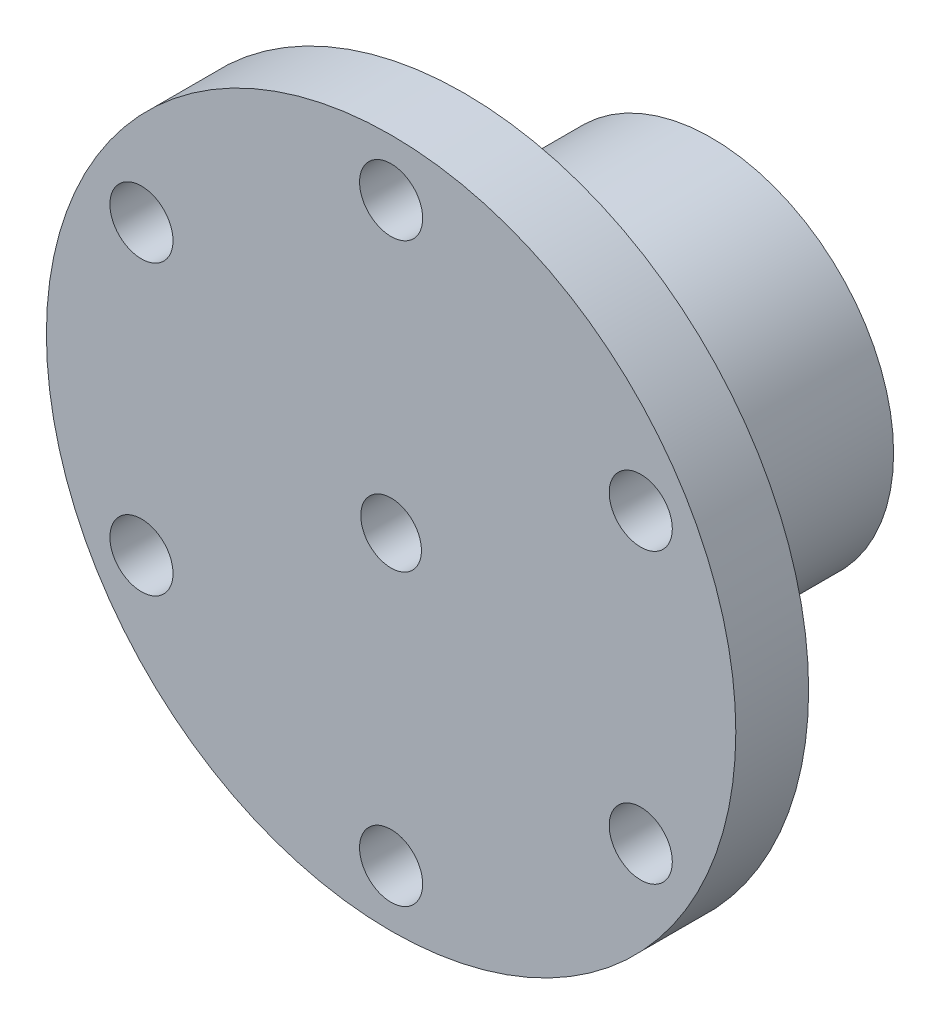
SolidWorks part; units mm, degrees
ref_plane "前视基准面" through (0, 0, 0) normal (0, 0, 1) x (1, 0, 0)
ref_plane "上视基准面" through (0, 0, 0) normal (0, 1, 0) x (1, 0, 0)
ref_plane "右视基准面" through (0, 0, 0) normal (1, 0, 0) x (0, 0, -1)
other "Configuration Table"
sketch "草图1" plane through (0, 0, 0) normal (0, 1, 0) x (1, 0, 0)
  line L0 (0, 0) -> (0, 26.4)
  line L1 (0, 26.4) -> (15, 26.4)
  line L2 (15, 26.4) -> (15, 6)
  line L3 (15, 6) -> (28.4, 6)
  line L4 (28.4, 6) -> (28.4, 0)
  line L5 (28.4, 0) -> (0, 0)
  dimension "D1" = 28.4
  dimension "D2" = 6
  dimension "D3" = 15
  dimension "D4" = 20.4
revolve "旋转1" add sketch "草图1" angle 360 about L0
sketch "草图2" plane through (0, 0, -26.4) normal (0, 0, -1) x (-1, 0, 0)
  circle A0 centre (0, 0) radius 2.5
  dimension "D1" = 5
extrude "切除-拉伸1" cut sketch "草图2" against normal through all
sketch "草图3" plane through (0, 0, 0) normal (0, 1, 0) x (1, 0, 0)
  circle A0 centre (0, 14.3702) radius 3
  dimension "D1" = 6
extrude "切除-拉伸2" cut sketch "草图3" against normal through all
sketch "草图4" plane through (0, 0, 0) normal (0, 0, 1) x (1, 0, 0)
  circle A12 centre (0, 23.75) radius 2.6
  circle A13 centre (20.5681, 11.875) radius 2.6
  circle A14 centre (20.5681, -11.875) radius 2.6
  circle A21 centre (0, -23.75) radius 2.6
  circle A22 centre (-20.5681, -11.875) radius 2.6
  circle A23 centre (-20.5681, 11.875) radius 2.6
  point P9 (0, 0)
  point P15 (0, 0)
  point P16 (0, 0)
  point P17 (0, 0)
  point P18 (0, 0)
  dimension "D1" = 5.2
  dimension "D2" = 23.75
  dimension "D3" = 6
extrude "切除-拉伸3" cut sketch "草图4" against normal through all
